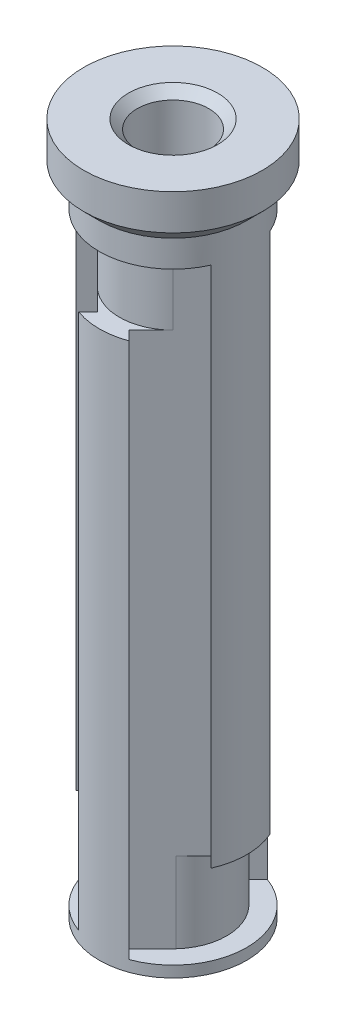
SolidWorks part; units mm, degrees
ref_plane "Front Plane" through (0, 0, 0) normal (0, 0, 1) x (1, 0, 0)
ref_plane "Top Plane" through (0, 0, 0) normal (0, 1, 0) x (1, 0, 0)
ref_plane "Right Plane" through (0, 0, 0) normal (1, 0, 0) x (0, 0, -1)
sketch "Sketch1" plane through (0, 0, 0) normal (0, 0, 1) x (1, 0, 0)
  line L0 (4, 0) -> (10, 0)
  line L1 (10, 0) -> (10, -4)
  line L2 (10, -4) -> (8.25, -5.75)
  line L3 (8.25, -5.75) -> (8.25, -77.5)
  line L4 (4, 0) -> (4, -80)
  line L5 (8.25, -77.5) -> (4, -77.5) construction
  line L6 (8.25, -77.5) -> (4, -80)
  line L8 (0, 0) -> (0, -84.1257) construction
  dimension "D1" = 6
  dimension "D2" = 4
  dimension "D3" = 4
  dimension "D4" = 1.75
  dimension "D5" = 1.75
  dimension "D6" = 71.75
  dimension "D7" = 80
revolve "Revolve1" add sketch "Sketch1" angle 360 about L8
ref_plane "Plane1" through (0, -8.75, 0) normal (0, 1, 0) x (1, 0, 0)
sketch "Sketch3" plane through (0, -8.75, 0) normal (0, 1, 0) x (1, 0, 0)
  line L0 (0, 0) -> (10, 0) construction
  line L1 (0, 0) -> (4.2426, -4.2426) construction
  line L2 (0, 0) -> (-4.2426, -4.2426) construction
  line L3 (4.2426, -4.2426) -> (6.364, -2.1213)
  line L4 (-4.2426, -4.2426) -> (-6.364, -2.1213)
  line L5 (6.364, -2.1213) -> (7.5556, -3.3129)
  line L6 (-6.364, -2.1213) -> (-7.5556, -3.3129)
  line L7 (0, 0) -> (-4.2426, 4.2426) construction
  line L8 (0, 0) -> (4.2426, 4.2426) construction
  line L9 (-6.364, 2.1213) -> (-7.5556, 3.3129)
  line L10 (6.364, 2.1213) -> (7.5556, 3.3129)
  line L11 (-4.2426, 4.2426) -> (-6.364, 2.1213)
  line L12 (4.2426, 4.2426) -> (6.364, 2.1213)
  circle A0 centre (0, 0) radius 10 construction
  arc A1 (4.2426, -4.2426) -> (-4.2426, -4.2426) centre (0, 0) cw
  circle A2 centre (0, 0) radius 8.25 construction
  circle A4 centre (0, 0) radius 8.25 construction
  arc A5 (7.5556, -3.3129) -> (-7.5556, -3.3129) centre (0, 0) cw
  arc A6 (7.5556, 3.3129) -> (-7.5556, 3.3129) centre (0, 0) ccw
  arc A7 (4.2426, 4.2426) -> (-4.2426, 4.2426) centre (0, 0) ccw
  dimension "D1" = 6
  dimension "D3" = 45
  dimension "D5" = 3
  dimension "D2" = 90
  dimension "D4" = 3
extrude "Cut-Extrude1" cut sketch "Sketch3" against normal blind 7.5 contours A7 L12 L10 A6 L9 L11 | A5 L5 L3 A1 L4 L6
sketch "Sketch4" plane through (0, -16.25, 0) normal (0, 1, 0) x (1, 0, 0)
  line L0 (2.8078, 7.7575) -> (1.7678, 6.7175)
  line L1 (6.364, 2.1213) -> (1.7678, 6.7175)
  line L2 (7.5556, 3.3129) -> (6.364, 2.1213)
  line L3 (-7.5556, 3.3129) -> (-6.364, 2.1213)
  line L4 (-6.364, 2.1213) -> (-1.7678, 6.7175)
  line L5 (-1.7678, 6.7175) -> (-2.8078, 7.7575)
  line L6 (4.2426, 4.2426) -> (6.364, 2.1213) construction
  line L7 (0, 0) -> (11.3802, 0) construction
  line L8 (-1.7678, -6.7175) -> (-2.8078, -7.7575)
  line L9 (-6.364, -2.1213) -> (-1.7678, -6.7175)
  line L10 (-7.5556, -3.3129) -> (-6.364, -2.1213)
  line L11 (7.5556, -3.3129) -> (6.364, -2.1213)
  line L12 (6.364, -2.1213) -> (1.7678, -6.7175)
  line L13 (2.8078, -7.7575) -> (1.7678, -6.7175)
  arc A0 (7.5556, 3.3129) -> (2.8078, 7.7575) centre (0, 0) ccw
  arc A1 (-7.5556, 3.3129) -> (-2.8078, 7.7575) centre (0, 0) cw
  arc A2 (7.5556, 3.3129) -> (-7.5556, 3.3129) centre (0, 0) ccw construction
  arc A4 (-7.5556, -3.3129) -> (-2.8078, -7.7575) centre (0, 0) ccw
  arc A5 (7.5556, -3.3129) -> (2.8078, -7.7575) centre (0, 0) cw
  dimension "D1" = 6.5
  dimension "D2" = 6.5
extrude "Cut-Extrude3" cut sketch "Sketch4" against normal blind 60
sketch "Sketch6" plane through (0, -76.25, 0) normal (0, 1, 0) x (1, 0, 0)
  line L0 (2.8078, 7.7575) -> (1.7678, 6.7175) construction
  line L1 (2.8078, -7.7575) -> (1.7678, -6.7175)
  line L2 (1.7678, -6.7175) -> (4.0659, -4.4194)
  line L3 (6.364, -2.1213) -> (1.7678, -6.7175) construction
  line L4 (1.7678, 6.7175) -> (6.364, 2.1213) construction
  line L5 (4.0659, 4.4194) -> (1.7678, 6.7175)
  line L6 (1.7678, 6.7175) -> (2.8078, 7.7575)
  line L7 (0, 0) -> (0, 10) construction
  line L8 (-1.7678, 6.7175) -> (-2.8078, 7.7575)
  line L9 (-4.0659, 4.4194) -> (-1.7678, 6.7175)
  line L10 (-1.7678, -6.7175) -> (-4.0659, -4.4194)
  line L11 (-2.8078, -7.7575) -> (-1.7678, -6.7175)
  arc A0 (2.8078, -7.7575) -> (2.8078, 7.7575) centre (0, 0) ccw
  arc A1 (4.0659, -4.4194) -> (4.0659, 4.4194) centre (0, 0) ccw
  circle A2 centre (0, 0) radius 10 construction
  arc A3 (-4.0659, -4.4194) -> (-4.0659, 4.4194) centre (0, 0) cw
  arc A4 (-2.8078, -7.7575) -> (-2.8078, 7.7575) centre (0, 0) cw
extrude "Cut-Extrude4" cut sketch "Sketch6" along normal blind 9
chamfer "Chamfer1" distance 1 angle 45 2 edges at (0, -80, 4) (0, 0, 4)
